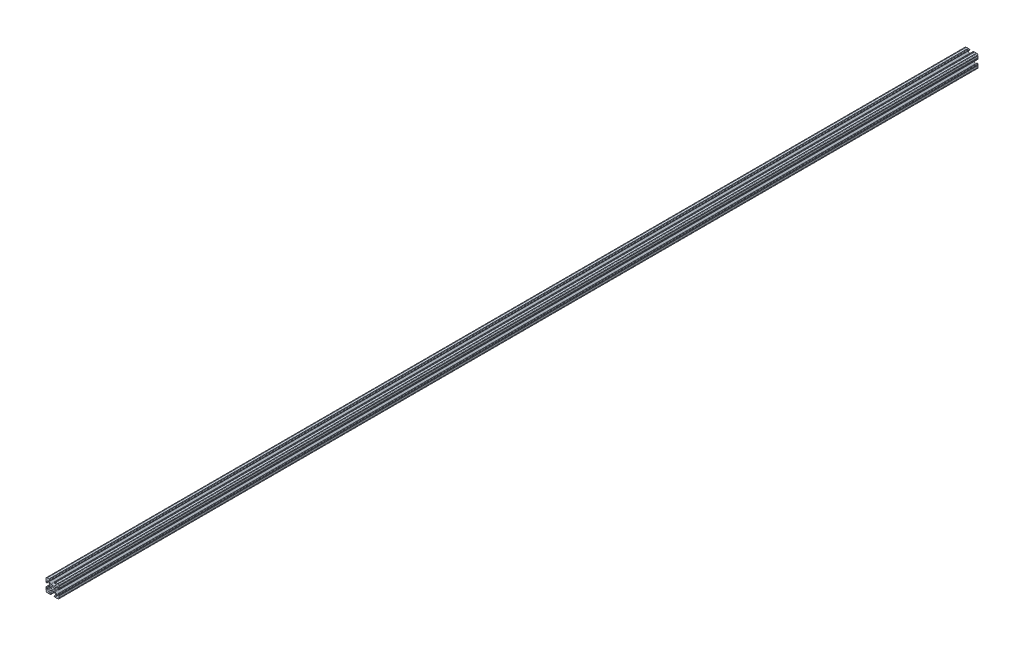
SolidWorks part; units mm, degrees
ref_plane "Front Plane" through (0, 0, 0) normal (0, 0, 1) x (1, 0, 0)
ref_plane "Top Plane" through (0, 0, 0) normal (0, 1, 0) x (1, 0, 0)
ref_plane "Right Plane" through (0, 0, 0) normal (1, 0, 0) x (0, 0, -1)
sketch "Sketch2" plane through (0, 0, 0) normal (0, 0, 1) x (1, 0, 0)
  line L0 (0, 12.7) -> (0, -12.7) construction
  line L1 (-12.7, 0) -> (12.7, 0) construction
  line L2 (3.2512, -12.7) -> (12.7, -12.7)
  line L3 (12.7, -12.7) -> (12.7, -3.2512)
  line L4 (3.2512, -12.7) -> (3.2512, -10.4902)
  line L5 (3.2512, -10.4902) -> (8.9276, -10.4902)
  line L6 (8.9276, -10.4902) -> (3.0856, -4.6482)
  line L7 (0, 0) -> (12.7, -12.7) construction
  line L8 (12.7, -3.2512) -> (10.4902, -3.2512)
  line L9 (10.4902, -3.2512) -> (10.4902, -8.9276)
  line L10 (10.4902, -8.9276) -> (4.6482, -3.0856)
  circle A0 centre (0, 0) radius 2.6035
  arc A1 (6.3485, -10.4902) -> (7.1039, -8.6665) centre (6.3485, -9.4219) ccw construction
  point P8 (0, -4.6482)
  dimension "Center Hole Diameter" = 5.207
  dimension "Rail Height" = 25.4
  dimension "Rail Width" = 25.4
  dimension "T-Slot Width" = 6.5024
  dimension "Slot Inner Width" = 14.8336
  dimension "Thickness" = 2.2098
  dimension "Slot Depth" = 5.842
  dimension "D1" = 2.2098
sketch "Sketch3" plane through (0, 0, 0) normal (1, 0, 0) x (0, 0, -1)
  line L0 (-1524, -12.7) -> (1524, -12.7) construction
  line L1 (-1498.6, 0) -> (1498.6, 0) construction
  dimension "Length" = 3048
  dimension "D1" = 25.4
sketch "Sketch4" plane through (0, 0, 0) normal (0, 0, 1) x (1, 0, 0)
  line L0 (4.1904, -12.7) -> (10.1173, -12.7)
  line L1 (3.2512, -12.7) -> (12.7, -12.7) construction
  line L2 (3.2512, -12.7) -> (3.2512, -10.4902) construction
  line L3 (3.2512, -10.4902) -> (8.9276, -10.4902) construction
  line L4 (3.2512, -11.4294) -> (3.2512, -11.7608)
  line L5 (4.1904, -10.4902) -> (6.3485, -10.4902)
  line L6 (0, -4.6482) -> (2.164, -4.6482)
  line L7 (8.9276, -10.4902) -> (3.0856, -4.6482) construction
  line L8 (3.7373, -5.2999) -> (7.1039, -8.6665)
  line L9 (12.7, -12.7) -> (12.7, -3.2512) construction
  line L10 (10.4902, -8.9276) -> (4.6482, -3.0856) construction
  line L11 (10.4902, -3.2512) -> (10.4902, -8.9276) construction
  line L12 (10.4902, -6.3485) -> (10.4902, -4.1904)
  line L13 (12.7, -3.2512) -> (10.4902, -3.2512) construction
  line L14 (11.4294, -3.2512) -> (11.7608, -3.2512)
  line L15 (12.7, -4.1904) -> (12.7, -10.1173)
  line L16 (8.6665, -7.1039) -> (5.2999, -3.7373)
  line L17 (4.6482, 0) -> (4.6482, -2.164)
  line L18 (-12.7, 0) -> (12.7, 0) construction
  line L19 (0, -4.6482) -> (0, -2.6035)
  line L20 (0, 12.7) -> (0, -12.7) construction
  line L21 (4.6482, 0) -> (2.6035, 0)
  arc A0 (3.2512, -11.7608) -> (4.1904, -12.7) centre (4.1904, -11.7608) ccw
  arc A2 (3.2512, -11.4294) -> (4.1904, -10.4902) centre (4.1904, -11.4294) cw
  arc A3 (6.3485, -10.4902) -> (7.1039, -8.6665) centre (6.3485, -9.4219) ccw
  arc A4 (2.164, -4.6482) -> (3.7373, -5.2999) centre (2.164, -6.8732) cw
  arc A5 (10.1173, -12.7) -> (12.7, -10.1173) centre (10.1173, -10.1173) ccw
  arc A6 (8.6665, -7.1039) -> (10.4902, -6.3485) centre (9.4219, -6.3485) ccw
  arc A7 (10.4902, -4.1904) -> (11.4294, -3.2512) centre (11.4294, -4.1904) cw
  arc A8 (11.7608, -3.2512) -> (12.7, -4.1904) centre (11.7608, -4.1904) cw
  arc A9 (5.2999, -3.7373) -> (4.6482, -2.164) centre (6.8732, -2.164) cw
  circle A10 centre (0, 0) radius 2.6035 construction
  arc A11 (0, -2.6035) -> (2.6035, 0) centre (0, 0) ccw
  dimension "D1" = 2.5827
  dimension "D2" = 2.225
  dimension "D3" = 0.9392
extrude "Boss-Extrude1" add sketch "Sketch4" along normal mid plane 3048
sketch "Sketch5" plane through (0, 0, 0) normal (0, 0, 1) x (1, 0, 0)
  line L0 (3.2512, -12.7) -> (12.7, -12.7) construction
  line L1 (4.1904, -10.4902) -> (6.3485, -10.4902) construction
  line L3 (0, 0) -> (12.7, -12.7) construction
  line L4 (6.3485, -10.4902) -> (6.3485, -12.7) construction
  line L5 (8.9276, -10.4902) -> (3.0856, -4.6482) construction
  circle A0 centre (10.3562, -12.7) radius 0.5524
  circle A1 centre (5.796, -12.7) radius 0.5524
  circle A2 centre (12.7, -10.3562) radius 0.5524
  circle A3 centre (12.7, -5.796) radius 0.5524
  point P10 (5.2694, -10.4902)
  point P12 (9.4219, -6.3485)
  dimension "D1" = 1.1049
extrude "Cut-Extrude1" cut sketch "Sketch5" against normal through all both and the other way through all
mirror "Mirror1" about plane through (0, 0, 0) normal (1, 0, 0) of bodies 137 134
mirror "Mirror2" about plane through (0, 0, 0) normal (0, 1, 0) of bodies 135
sketch "Sketch8" plane through (0, 0, 0) normal (0, 1, 0) x (1, 0, 0)
  line L0 (-12.58, 1524) -> (-12.58, -1524) construction
  line L1 (-25.28, 1536.7) -> (25.28, 1536.7)
  line L2 (-25.28, 1536.7) -> (-25.28, 254)
  line L3 (-25.28, 254) -> (25.28, 254)
  line L4 (25.28, 1536.7) -> (25.28, 254)
  line L5 (12.58, 1524) -> (12.58, -1524) construction
  line L7 (-6.3485, -1524) -> (-9.8037, -1524) construction
  dimension "D1" = 12.7
  dimension "D2" = 12.7
  dimension "D3" = 12.7
  dimension "D4" = 1778
extrude "Cut-Extrude2" cut sketch "Sketch8" against normal through all both and the other way through all
equation "\"D1@Boss-Extrude1\"=\"Length@Sketch3\""
equation "\"D1@Sketch2\"=\"Thickness@Sketch2\""
equation "\"D2@Sketch4\"=\"Slot Inner Width@Sketch2\"*0.15"
equation "\"D1@Sketch4\"=\"D3@Sketch4\"*2.75"
equation "\"D3@Sketch4\"=\"Thickness@Sketch2\"*0.425"
equation "\"D1@Sketch5\"=\"Thickness@Sketch2\"*0.5"
